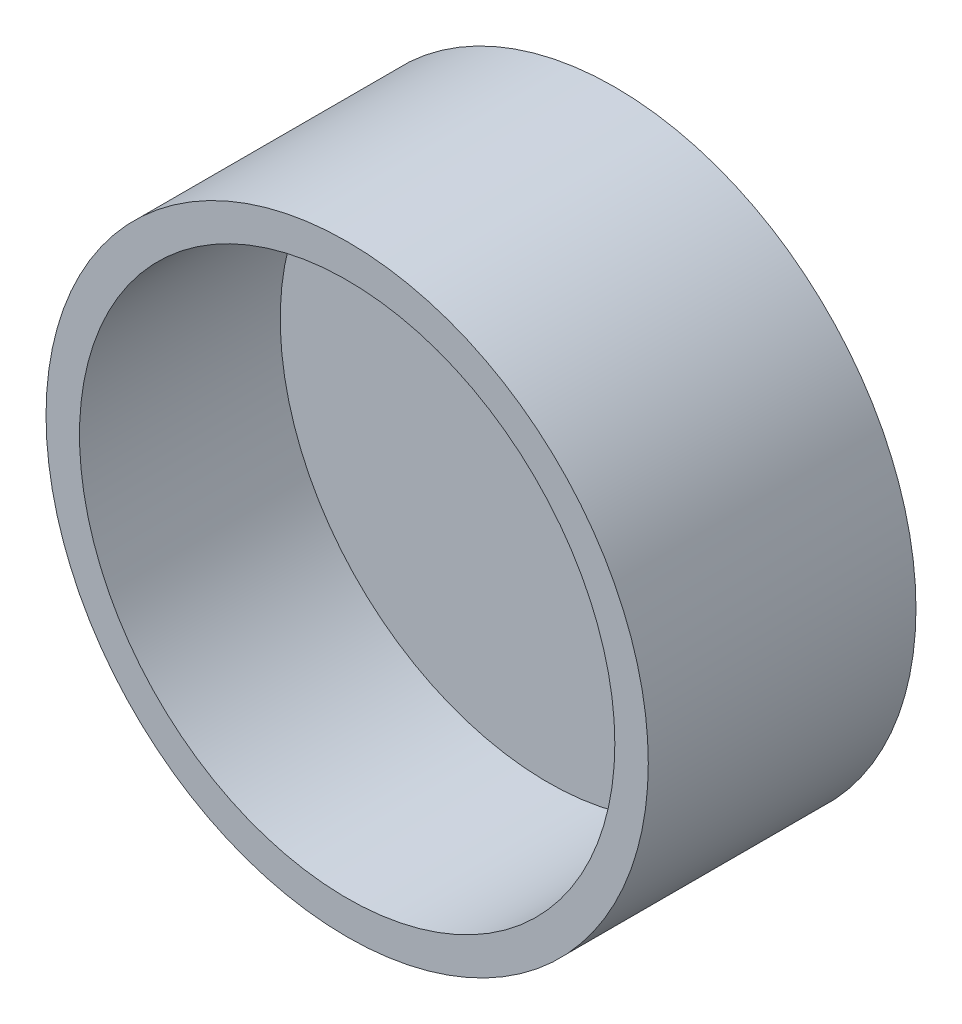
SolidWorks part; units mm, degrees
ref_plane "Front Plane" through (0, 0, 0) normal (0, 0, 1) x (1, 0, 0)
ref_plane "Top Plane" through (0, 0, 0) normal (0, 1, 0) x (1, 0, 0)
ref_plane "Right Plane" through (0, 0, 0) normal (1, 0, 0) x (0, 0, -1)
sketch "Sketch1" plane through (0, 0, 0) normal (0, 0, 1) x (1, 0, 0)
  circle A0 centre (0, 0) radius 22.5
  dimension "D1" = 45
extrude "Boss-Extrude1" add sketch "Sketch1" along normal blind 20
sketch "Sketch2" plane through (0, 0, 20) normal (0, 0, 1) x (1, 0, 0)
  circle A0 centre (0, 0) radius 20
  dimension "D1" = 40
extrude "Cut-Extrude1" cut sketch "Sketch2" against normal blind 15
